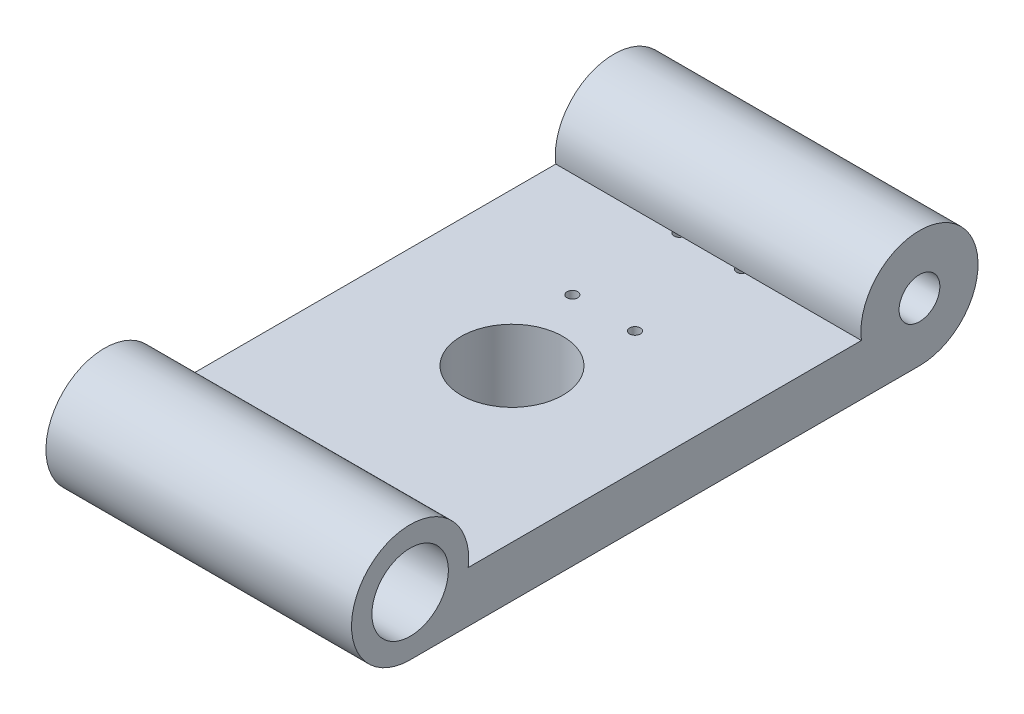
SolidWorks part; units mm, degrees
ref_plane "Front Plane" through (0, 0, 0) normal (0, 0, 1) x (1, 0, 0)
ref_plane "Top Plane" through (0, 0, 0) normal (0, 1, 0) x (1, 0, 0)
ref_plane "Right Plane" through (0, 0, 0) normal (1, 0, 0) x (0, 0, -1)
sketch "Sketch1" plane through (0, 0, 0) normal (1, 0, 0) x (0, 0, -1)
  line L0 (-38.5982, -1.5) -> (38.5982, -1.5)
  line L1 (-50, -11.5) -> (50, -11.5)
  circle A0 centre (-50, 0) radius 7.5
  circle A1 centre (50, 0) radius 4
  arc A2 (-38.5982, -1.5) -> (-50, -11.5) centre (-50, 0) ccw
  arc A3 (50, -11.5) -> (38.5982, -1.5) centre (50, 0) ccw
  dimension "D1" = 100
  dimension "D2" = 50
  dimension "D3" = 8
  dimension "D6" = 15
  dimension "D5" = 11.5
  dimension "D4" = 10
extrude "Boss-Extrude1" add sketch "Sketch1" along normal mid plane 60 contours L1 A3 L0 A2 A0 A1
sketch "Sketch2" plane through (0, 0, 0) normal (1, 0, 0) x (0, 0, -1)
  line L0 (0, -11.5) -> (15, -11.5)
  line L4 (15, -11.5) -> (15, -24)
  line L5 (15, -24) -> (0, -24)
  line L8 (0, -24) -> (0, -11.5)
  line L9 (-50, -11.5) -> (50, -11.5) construction
  point P2 (0, 0)
  point P3 (0, 0)
  point P4 (0, 0)
  point P5 (15, -11.5)
  point P9 (0, -24.6382)
  point P10 (15, -11.9779)
  point P11 (0, -11.5)
  point P12 (0, -24)
  point P15 (0, -23.816)
  dimension "D1" = 12.5
  dimension "D5" = 15
revolve "Revolve1" add sketch "Sketch2" angle 360 about L8
sketch "Sketch3" plane through (0, -1.5, 0) normal (0, 1, 0) x (1, 0, 0)
  circle A0 centre (0, 0) radius 10
  dimension "D1" = 20
extrude "Cut-Extrude1" cut sketch "Sketch3" against normal through all
sketch "Sketch4" plane through (0, -11.5, 0) normal (0, -1, 0) x (1, 0, 0)
  circle A0 centre (-6.15, -18) radius 1.05
  circle A1 centre (-6.15, -39) radius 1.05
  circle A2 centre (6.15, -18) radius 1.05
  circle A3 centre (6.15, -39) radius 1.05
  point P8 (0, 0)
  point P9 (0, 0)
  point P10 (0, 0)
  point P11 (0, 0)
  dimension "D4" = 2.1
  dimension "D1" = 21
  dimension "D2" = 12.3
  dimension "D3" = 6.15
  dimension "D5" = 18
extrude "Cut-Extrude2" cut sketch "Sketch4" against normal blind 10
